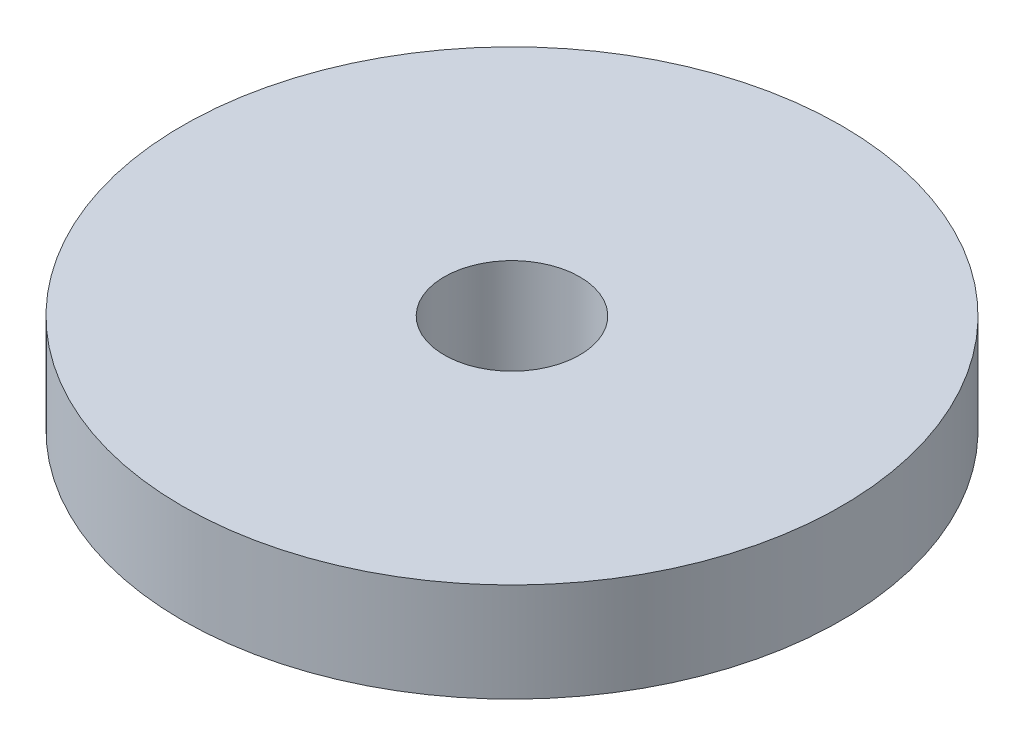
SolidWorks part; units mm, degrees
ref_plane "Front Plane" through (0, 0, 0) normal (0, 0, 1) x (1, 0, 0)
ref_plane "Top Plane" through (0, 0, 0) normal (0, 1, 0) x (1, 0, 0)
ref_plane "Right Plane" through (0, 0, 0) normal (1, 0, 0) x (0, 0, -1)
sketch "Sketch1" plane through (0, 0, 0) normal (0, 1, 0) x (1, 0, 0)
  circle A0 centre (0, 0) radius 15.875
  circle A1 centre (0, 0) radius 3.2639
  dimension "D1" = 6.5278
  dimension "D2" = 31.75
extrude "Boss-Extrude1" add sketch "Sketch1" along normal blind 4.7625
equation "\"Outer Diameter\"= 1.25"
equation "\"Washer Thickness\"= 0.1875"
equation "\"Inner Diameter\"= 0.257"
equation "\"D2@Sketch1\"=\"Outer Diameter\""
equation "\"D1@Sketch1\"=\"Inner Diameter\""
equation "\"D1@Boss-Extrude1\"=\"Washer Thickness\""
